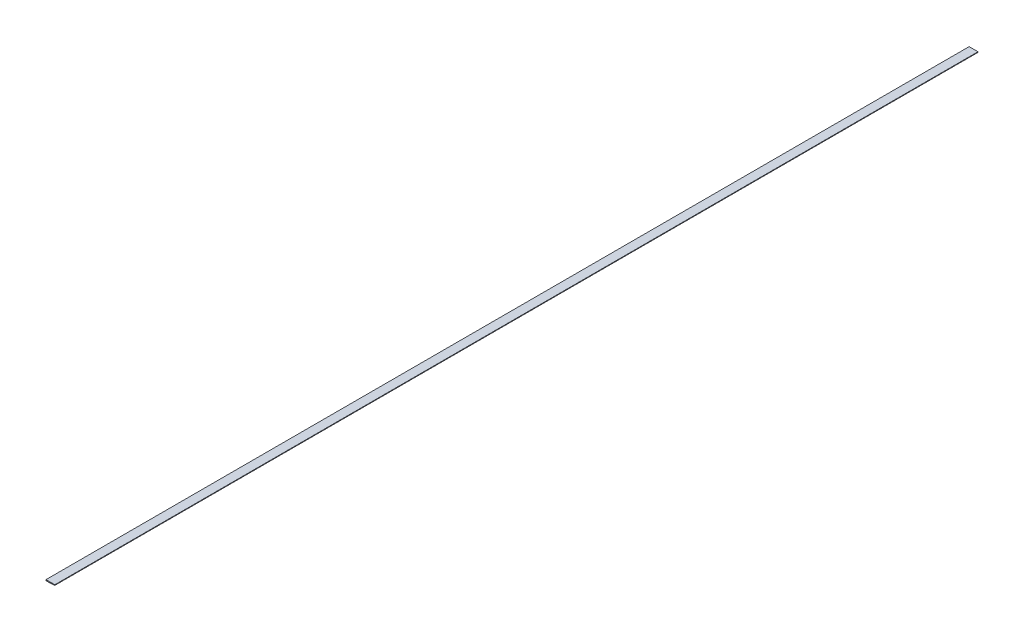
SolidWorks part; units mm, degrees
material "ASTM A500 Grade B Steel"
ref_plane "Front Plane" through (0, 0, 0) normal (0, 0, 1) x (1, 0, 0)
ref_plane "Top Plane" through (0, 0, 0) normal (0, 1, 0) x (1, 0, 0)
ref_plane "Right Plane" through (0, 0, 0) normal (1, 0, 0) x (0, 0, -1)
sketch "Sketch2" plane through (0, 0, 0) normal (0, 0, 1) x (1, 0, 0)
  line L0 (2095.63, 25.4) -> (2070.63, 25.4)
  line L1 (0, 25.4) -> (2095.63, 25.4) construction
  line L2 (2070.63, 25.4) -> (2070.63, 30.8407)
  line L3 (2095.63, 25.4) -> (2108.2455, 26.5037)
  line L4 (2101.9558, 25.9534) -> (4194.418, 209.0202) construction
  line L5 (2120.63, 30.8407) -> (2120.63, 27.5872)
  line L6 (2120.63, 30.8407) -> (2070.63, 30.8407)
  line L7 (2108.2455, 26.5037) -> (2120.63, 27.5872)
  dimension "D1" = 25
  dimension "D2" = 25
extrude "Boss-Extrude1" add sketch "Sketch2" against normal up to surface (5214.4 mm away)
